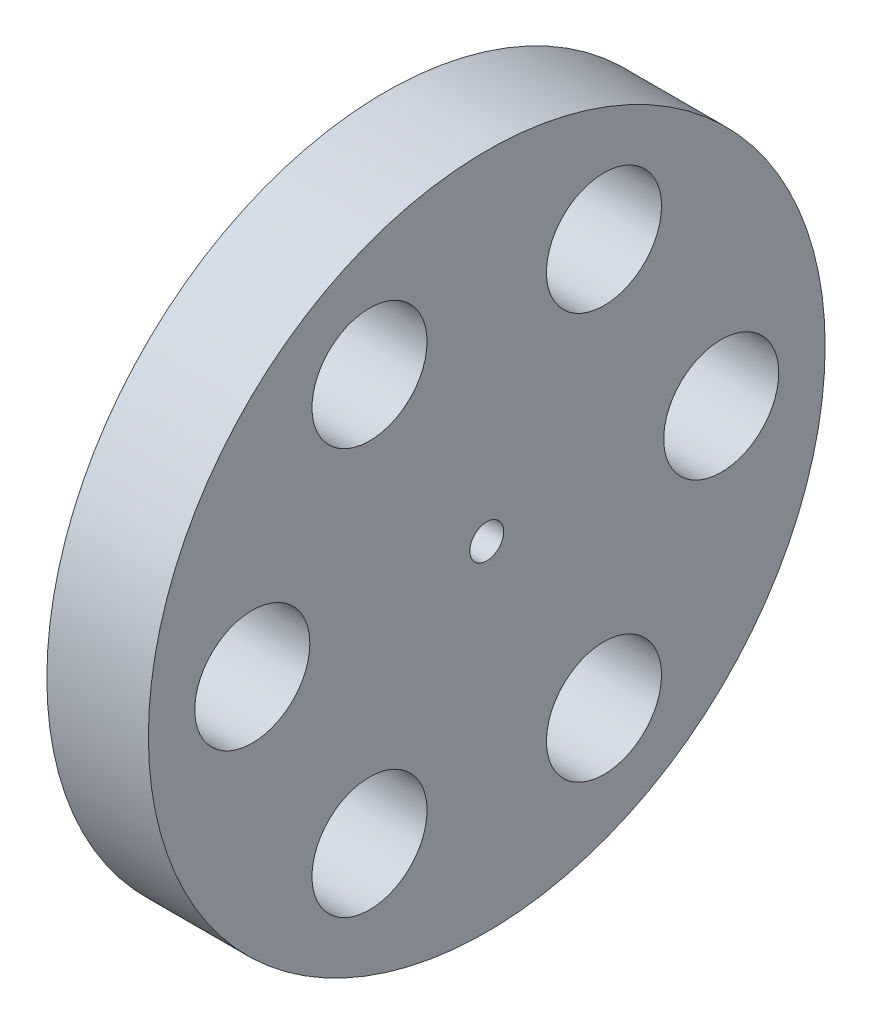
SolidWorks part; units mm, degrees
ref_plane "前基準面" through (0, 0, 0) normal (0, 0, 1) x (1, 0, 0)
ref_plane "上基準面" through (0, 0, 0) normal (0, 1, 0) x (1, 0, 0)
ref_plane "右基準面" through (0, 0, 0) normal (1, 0, 0) x (0, 0, -1)
sketch "草圖1" plane through (0, 0, 0) normal (1, 0, 0) x (0, 0, -1)
  line L1 (17.3205, -30) -> (34.641, 0)
  line L2 (34.641, 0) -> (17.3205, 30)
  line L3 (17.3205, 30) -> (-17.3205, 30)
  line L4 (-17.3205, 30) -> (-34.641, 0)
  line L5 (-34.641, 0) -> (-17.3205, -30)
  line L6 (-17.3205, -30) -> (17.3205, -30)
  circle A0 centre (0, 0) radius 50
  circle A1 centre (0, 0) radius 30 construction
  circle A2 centre (17.3205, 30) radius 8.5
  circle A3 centre (34.641, 0) radius 8.5
  circle A4 centre (17.3205, -30) radius 8.5
  circle A5 centre (-17.3205, -30) radius 8.5
  circle A6 centre (-34.641, 0) radius 8.5
  circle A7 centre (-17.3205, 30) radius 8.5
  circle A8 centre (0, 0) radius 2.5
  dimension "D1" = 100
  dimension "D3" = 60
  dimension "D4" = 17
  dimension "D5" = 5
  dimension "D2" = 30
extrude "填料-伸長1" add sketch "草圖1" along normal blind 15 contours A0 A7 L3 A2 L2 A3 L1 A4 L6 A5 L5 A6 L4 | A7 L4 A6 L5 A5 L6 A4 L1 A3 L2 A2 L3 A8
